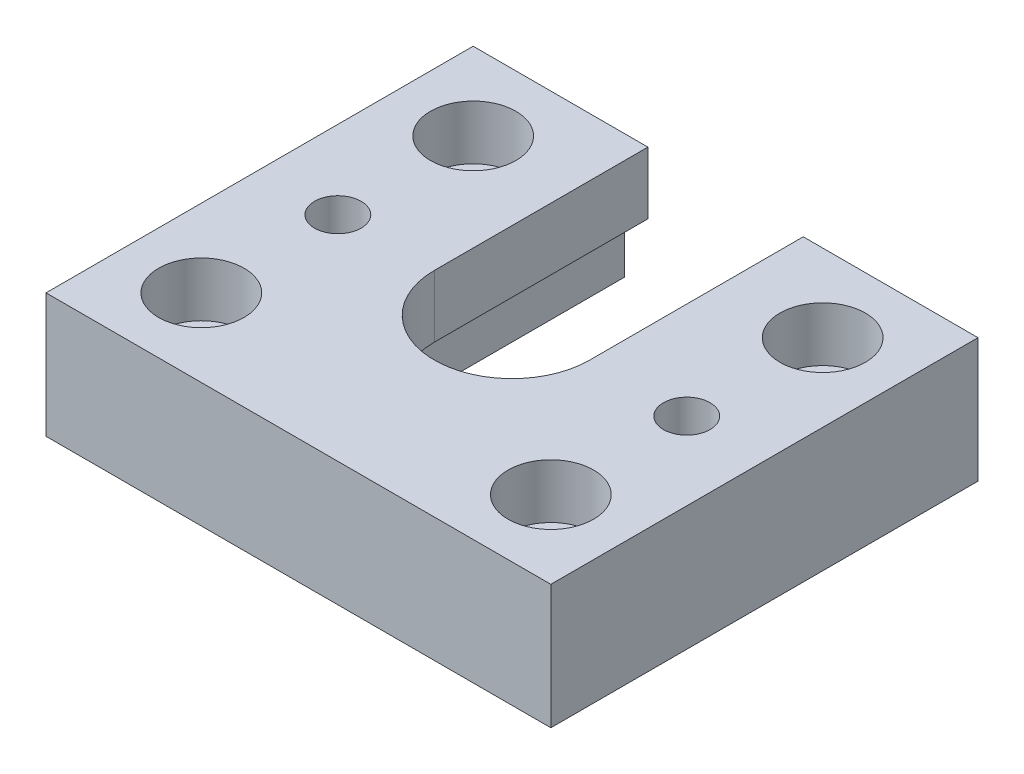
SolidWorks part; units mm, degrees
ref_plane "Front Plane" through (0, 0, 0) normal (0, 0, 1) x (1, 0, 0)
ref_plane "Top Plane" through (0, 0, 0) normal (0, 1, 0) x (1, 0, 0)
ref_plane "Right Plane" through (0, 0, 0) normal (1, 0, 0) x (0, 0, -1)
sketch "Sketch1" plane through (0, 0, 0) normal (0, 1, 0) x (1, 0, 0)
  line L0 (32.5, 55) -> (32.5, 0) construction
  line L1 (0, 0) -> (65, 0)
  line L2 (0, 0) -> (0, 55)
  line L3 (0, 55) -> (65, 55)
  line L4 (65, 0) -> (65, 55)
  line L5 (0, 27.5) -> (65, 27.5) construction
  dimension "D1" = 55
  dimension "D2" = 65
extrude "Boss-Extrude1" add sketch "Sketch1" along normal blind 16
hole_wizard "CBORE SLOT for M6 Hex Socket Head Cap Screw1" positions "Sketch8" profile "Sketch4" size "M6" standard "ISO" slot yes end condition through all
sketch "Sketch8" plane through (0, 16, 0) normal (0, 1, 0) x (1, 0, 0)
  line L0 (32.5, 55) -> (32.5, 0) construction
  line L1 (0, 27.5) -> (65, 27.5) construction
  point P5 (10, 45)
  point P7 (55, 45)
  point P9 (55, 10)
  point P11 (10, 10)
  dimension "D1" = 22.5
  dimension "D2" = 45
  dimension "D3" = 17.5
  dimension "D4" = 35
sketch "Sketch4" plane through (10, 16, -45) normal (1, 0, 0) x (0, 0, 1)
  line L0 (0, 0) -> (0, 16)
  line L1 (0, 16) -> (3.3, 16)
  line L3 (3.3, 16) -> (3.3, 7)
  line L4 (3.3, 7) -> (5.5, 7)
  line L5 (5.5, 7) -> (5.5, 0)
  line L7 (5.5, 0) -> (0, 0)
  line L11 (0, -6.35) -> (0, 107.95) construction
  dimension "Thru Hole Dia." = 6.6
  dimension "Thru Hole Depth" = 16
  dimension "C'Bore Dia." = 11
  dimension "C'Bore Depth" = 7
hole_wizard "Ø6.0mm Dowel Hole1" positions "Sketch10" profile "Sketch11" hole size "Ø6.0" standard "ISO" end condition through all
sketch "Sketch10" plane through (0, 16, 0) normal (0, 1, 0) x (1, 0, 0)
  line L0 (0, 27.5) -> (65, 27.5) construction
  line L1 (0, 55) -> (65, 55) construction
  circle A0 centre (10, 45) radius 3.3 construction
  point P0 (10.0781, 27.5)
  point P4 (55, 27.5)
  dimension "D1" = 17.5
  dimension "D2" = 27.5
sketch "Sketch11" plane through (10.0781, 16, -27.5) normal (1, 0, 0) x (0, 0, 1)
  line L0 (0, 0) -> (0, 16)
  line L1 (0, 16) -> (3, 16)
  line L2 (3, 16) -> (3, 0)
  line L5 (3, 0) -> (0, 0)
  line L11 (0, -6.35) -> (0, 107.95) construction
  dimension "Thru Hole Dia." = 6
  dimension "Thru Hole Depth" = 16
ref_plane "Plane1" through (0, 8, 0) normal (0, 1, 0) x (1, 0, 0)
sketch "Sketch21" plane through (0, 0, 0) normal (0, -1, 0) x (1, 0, 0)
  line L0 (32.5, -55) -> (32.5, 0) construction
  line L1 (45.5, -27.5) -> (45.5, -55)
  line L2 (0, -55) -> (65, -55) construction
  line L3 (19.5, -27.5) -> (19.5, -55)
  circle A0 centre (32.5, -27.5) radius 13
  dimension "D1" = 26
sketch "Sketch22" plane through (0, 0, 0) normal (0, -1, 0) x (1, 0, 0)
  line L4 (0, 0) -> (0, -55)
  line L5 (0, -55) -> (65, -55)
  line L6 (65, -55) -> (65, 0)
  line L7 (65, 0) -> (0, 0)
  line L8 (0, 0) -> (0, -55)
  line L9 (0, -55) -> (65, -55)
  line L10 (65, -55) -> (65, 0)
  line L11 (65, 0) -> (0, 0)
  dimension "D1" = 0
sketch "Sketch23" plane through (0, 0, 0) normal (0, -1, 0) x (1, 0, 0)
  line L0 (19.5, -27.5) -> (19.5, -55) construction
  line L1 (19.5, -27.5) -> (19.5, -55)
  line L2 (45.5, -27.5) -> (45.5, -55) construction
  line L3 (45.5, -27.5) -> (45.5, -55)
  line L4 (0, -55) -> (65, -55) construction
  line L5 (0, -55) -> (65, -55)
  circle A0 centre (32.5, -27.5) radius 13 construction
  circle A1 centre (32.5, -27.5) radius 13
  line M9 (0, -55) -> (65, -55)
extrude "Cut-Extrude2" cut sketch "Sketch23" against normal blind 8 contours A1 L1 L3 M9 | A1
sketch "Sketch24" plane through (0, 8, 0) normal (0, -1, 0) x (1, 0, 0)
  line L0 (32.5, -55) -> (32.5, 0) construction
  line L1 (42.5, -27.5) -> (42.5, -55)
  line L2 (0, -55) -> (65, -55) construction
  line L3 (22.5, -27.5) -> (22.5, -55)
  line L4 (0, -55) -> (65, -55)
  circle A0 centre (32.5, -27.5) radius 10
  line M6 (19.5, -55) -> (45.5, -55)
  dimension "D1" = 20
extrude "Cut-Extrude3" cut sketch "Sketch24" against normal through all contours A0 | A0 L3 L1 M6
